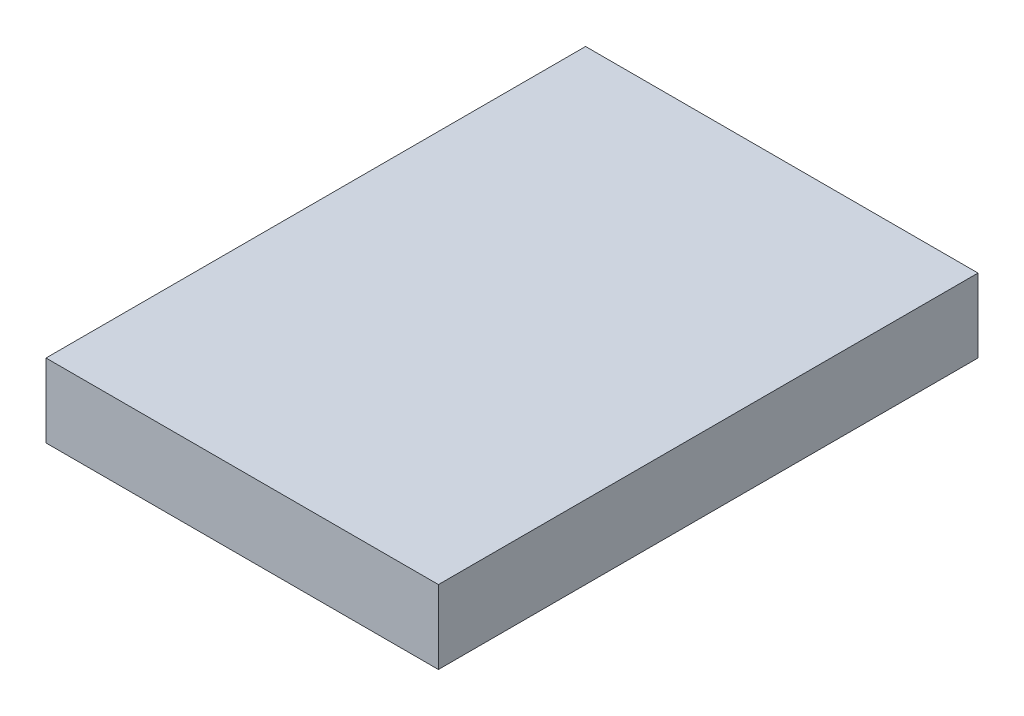
SolidWorks part; units mm, degrees
ref_plane "Front Plane" through (0, 0, 0) normal (0, 0, 1) x (1, 0, 0)
ref_plane "Top Plane" through (0, 0, 0) normal (0, 1, 0) x (1, 0, 0)
ref_plane "Right Plane" through (0, 0, 0) normal (1, 0, 0) x (0, 0, -1)
sketch "Sketch1" plane through (0, 0, 0) normal (0, 1, 0) x (1, 0, 0)
  line L1 (-50.8, -69.85) -> (50.8, -69.85)
  line L2 (-50.8, -69.85) -> (-50.8, 69.85)
  line L3 (-50.8, 69.85) -> (50.8, 69.85)
  line L4 (50.8, -69.85) -> (50.8, 69.85)
  line L5 (-50.8, -69.85) -> (50.8, 69.85) construction
  line L6 (-50.8, 69.85) -> (50.8, -69.85) construction
  point P0 (0, 0)
  dimension "D1" = 101.6
  dimension "D2" = 139.7
extrude "Boss-Extrude1" add sketch "Sketch1" against normal blind 19.05
